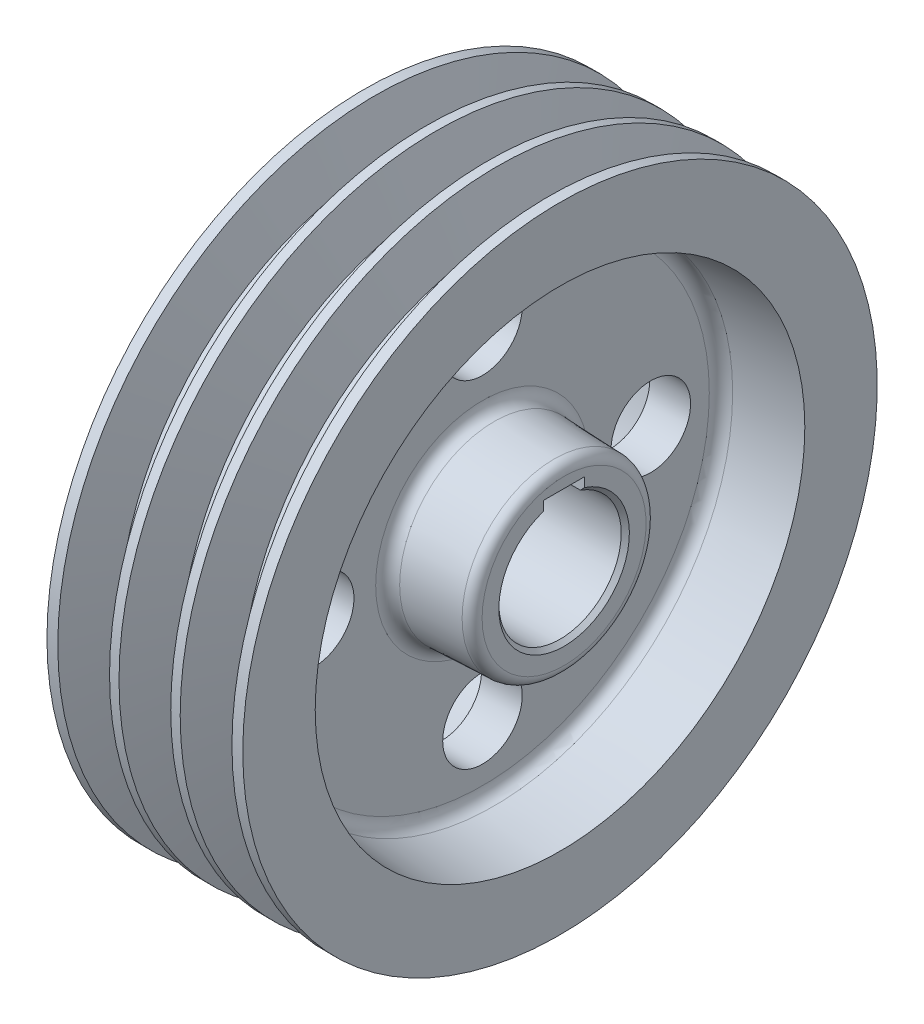
SolidWorks part; units mm, degrees
ref_plane "前视基准面" through (0, 0, 0) normal (0, 0, 1) x (1, 0, 0)
ref_plane "上视基准面" through (0, 0, 0) normal (0, 1, 0) x (1, 0, 0)
ref_plane "右视基准面" through (0, 0, 0) normal (1, 0, 0) x (0, 0, -1)
sketch "草图1" plane through (0, 0, 0) normal (0, 0, 1) x (1, 0, 0)
  line L0 (0, 0) -> (64.8368, 0) construction
  line L1 (-1, 15) -> (-1, 22.5)
  line L2 (0, 77.75) -> (48, 77.75)
  line L3 (48, 77.75) -> (48, 60)
  line L4 (-1, 22.5) -> (-30, 22.5) construction
  line L5 (19, 24.2498) -> (19, 59.2402)
  line L6 (49, 15) -> (-1, 15)
  line L7 (2.6592, 77.75) -> (6.1599, 66.3) construction
  line L8 (6.1599, 66.3) -> (11.8401, 66.3) construction
  line L9 (11.8401, 66.3) -> (15.3408, 77.75) construction
  line L10 (0, 75) -> (48, 75) construction
  line L11 (9, 66.3) -> (9, 15) construction
  line L12 (44, 60) -> (0, 60) construction
  line L13 (48, 60) -> (79, 60) construction
  line L14 (29, 58.3377) -> (29, 23.2998)
  line L15 (5, 22.5) -> (49, 22.5) construction
  line L16 (24, 15) -> (24, 77.75) construction
  line L17 (49, 22.5) -> (49, 15)
  line L18 (0, 60) -> (0, 77.75)
  line L19 (19, 51) -> (29, 51) construction
  line L20 (19, 31.5) -> (29, 31.5) construction
  line L21 (48, 60) -> (48, 51) construction
  line L22 (48, 51) -> (29, 51) construction
  line L23 (29, 31.5) -> (49, 31.5) construction
  line L24 (49, 31.5) -> (49, 22.5) construction
  line L25 (29, 58.3377) -> (48, 60)
  line L26 (19, 59.2402) -> (0, 60)
  line L27 (19, 24.2498) -> (-1, 22.5)
  line L28 (29, 23.2998) -> (49, 22.5)
  point P17 (3.5, 75)
  point P18 (14.5, 75)
  dimension "d2" = 120
  dimension "L" = 50
  dimension "B" = 48
  dimension "d" = 30
  dimension "d1" = 45
  dimension "D3" = 5
  dimension "D4" = 2.29
  dimension "dd" = 150
  dimension "f" = 9
  dimension "槽轮角" = 34
  dimension "bd" = 11
  dimension "hf" = 8.7
  dimension "ha" = 2.75
  dimension "da" = 155.5
  dimension "S" = 10
  dimension "S2" = 9
revolve "旋转1" add sketch "草图1" angle 360 about L0
sketch "草图2" plane through (0, 0, 0) normal (0, 0, 1) x (1, 0, 0)
  line L0 (11.8401, 66.3) -> (15.3408, 77.75) construction
  line L1 (6.1599, 66.3) -> (11.8401, 66.3) construction
  line L2 (2.6592, 77.75) -> (6.1599, 66.3) construction
  line L3 (11.8401, 66.3) -> (15.3408, 77.75)
  line L4 (6.1599, 66.3) -> (11.8401, 66.3)
  line L5 (2.6592, 77.75) -> (6.1599, 66.3)
  line L6 (2.6592, 77.75) -> (15.3408, 77.75)
  line L7 (0, 0) -> (123, 0) construction
revolve "切除-旋转1" cut sketch "草图2" angle 360 about L7
pattern_linear "轮槽数" count 3 spacing 15 along (1, 0, 0) of "切除-旋转1"
chamfer "倒角1" distance 1 2 edges at (-1, 0, 15) (49, 0, 15)
sketch "草图4" plane through (-1, 0, 0) normal (-1, 0, 0) x (0, 0, 1)
  line L1 (-5, 14.1421) -> (5, 14.1421)
  line L2 (-5, 14.1421) -> (-5, 17.5)
  line L3 (-5, 17.5) -> (5, 17.5)
  line L4 (5, 14.1421) -> (5, 17.5)
  circle A0 centre (0, 0) radius 15 construction
  point P6 (2.5, 17.5)
  dimension "键槽高度" = 17.5
  dimension "键槽宽度" = 10
  dimension "t1" = 2.5
extrude "切除-拉伸1" cut sketch "草图4" against normal through all
fillet "圆角1" radius 3 4 edges at (29, 0, 58.3377) (19, 0, 24.2498) (19, 0, 59.2402) (29, 0, 23.2998)
fillet "圆角2" radius 2.5 2 edges at (49, 0, 22.5) (-1, 0, 22.5)
sketch "草图5" plane through (0, 0, 0) normal (1, 0, 0) x (0, 0, -1)
  line L0 (0, 66.3) -> (0, 15) construction
  circle A0 centre (0, 41.25) radius 9.75
extrude "切除-拉伸2" cut sketch "草图5" along normal through all
pattern_circular "圆孔个数" count 4 over 360 about axis through (0, 0, 0) along (1, 0, 0) of "切除-拉伸2"
equation "\"B@草图1\" =  ( \"z@轮槽数\" - 1 )  * \"e@轮槽数\" +2 *  \"f@草图1\""
equation "\"键槽高度@草图4\" = \"d@草图1\" / 2 + \"t1@草图4\""
